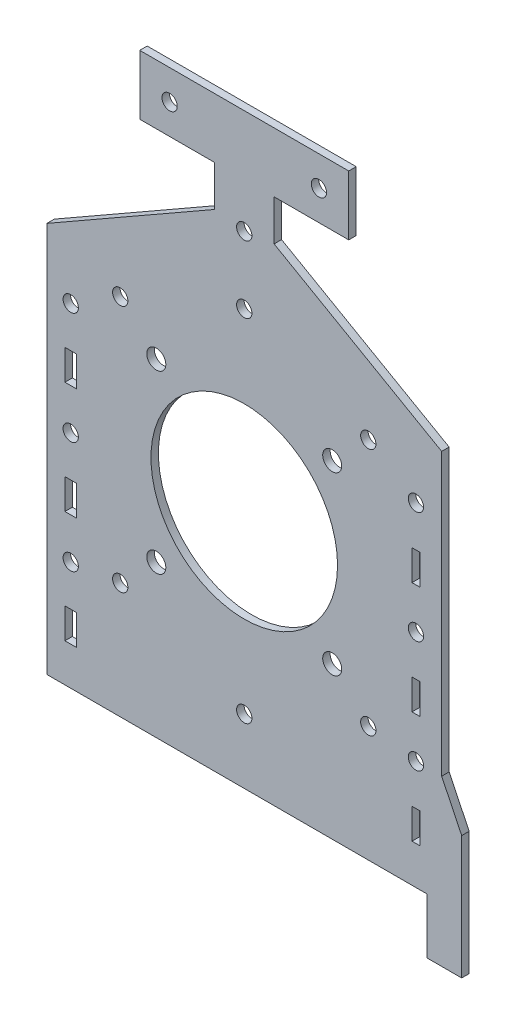
SolidWorks part; units mm, degrees
ref_plane "前视基准面" through (0, 0, 0) normal (0, 0, 1) x (1, 0, 0)
ref_plane "上视基准面" through (0, 0, 0) normal (0, 1, 0) x (1, 0, 0)
ref_plane "右视基准面" through (0, 0, 0) normal (1, 0, 0) x (0, 0, -1)
sketch "草图1" plane through (0, 0, 0) normal (0, 0, 1) x (1, 0, 0)
  line L0 (0, -36.5) -> (-46, -36.5) construction
  line L1 (52.9, 53.8832) -> (52.9, -21.5)
  line L29 (-52.9, 53.8832) -> (-52.9, -50.79)
  line L32 (0, 63.5) -> (0, -36.5) construction
  line L33 (-23.57, 37.07) -> (-23.57, -10.07) construction
  line L34 (23.57, 37.07) -> (23.57, -10.07) construction
  line L52 (-52.9, 53.8832) -> (52.9, 53.8832) construction
  line L60 (0, 78.5) -> (0, 84.5) construction
  line L61 (-28, 106.5) -> (28, 106.5)
  line L62 (28, 106.5) -> (28, 90.5)
  line L63 (28, 90.5) -> (8, 90.5)
  line L64 (8, 90.5) -> (8, 79.5697)
  line L65 (-28, 106.5) -> (-28, 90.5)
  line L66 (-28, 90.5) -> (-8, 90.5)
  line L67 (-8, 90.5) -> (-8, 79.5697)
  line L69 (48.9187, -50.79) -> (48.9187, -65.6422)
  line L70 (48.9187, -65.6422) -> (58.27, -65.6422)
  line L75 (58.27, -65.6422) -> (58.27, -32.5909)
  line L76 (-52.9, 53.8832) -> (-8, 79.5697)
  line L77 (8, 79.5697) -> (52.9, 53.8832)
  line L78 (46, 8.5) -> (43.95, 8.5) construction
  line L79 (47.05, 19.45) -> (44.95, 27.55) construction
  line L80 (47.05, 27.55) -> (44.95, 19.45) construction
  line L81 (46, -6.5) -> (44.95, -6.5) construction
  line L82 (47.05, -10.55) -> (44.95, -2.45) construction
  line L83 (47.05, -2.45) -> (44.95, -10.55) construction
  line L84 (47.05, -40.55) -> (44.95, -32.45) construction
  line L85 (47.05, -32.45) -> (44.95, -40.55) construction
  line L86 (46, -21.5) -> (43.95, -21.5) construction
  line L87 (47.05, 19.45) -> (44.95, 19.45)
  line L88 (47.05, 19.45) -> (47.05, 27.55)
  line L89 (47.05, 27.55) -> (44.95, 27.55)
  line L90 (44.95, 19.45) -> (44.95, 27.55)
  line L91 (47.05, -10.55) -> (44.95, -10.55)
  line L92 (47.05, -10.55) -> (47.05, -2.45)
  line L93 (47.05, -2.45) -> (44.95, -2.45)
  line L94 (44.95, -10.55) -> (44.95, -2.45)
  line L95 (44.95, -32.45) -> (44.95, -40.55)
  line L96 (47.05, -40.55) -> (44.95, -40.55)
  line L97 (47.05, -32.45) -> (47.05, -40.55)
  line L98 (47.05, -32.45) -> (44.95, -32.45)
  line L99 (58.27, -32.5909) -> (52.9, -21.5)
  line L101 (-44.95, 27.55) -> (-48.05, 27.55)
  line L122 (-52.9, -50.79) -> (-43.7092, -50.79)
  line L126 (-34.4034, -50.79) -> (48.9187, -50.79)
  line L131 (-43.7092, -50.79) -> (-34.4034, -50.79)
  line L139 (-44.95, 19.45) -> (-48.05, 19.45)
  line L140 (-44.95, 27.55) -> (-44.95, 19.45)
  line L141 (-48.05, 27.55) -> (-48.05, 19.45)
  line L142 (-44.95, -2.45) -> (-44.95, -10.55)
  line L143 (-44.95, -10.55) -> (-48.05, -10.55)
  line L144 (-44.95, -2.45) -> (-48.05, -2.45)
  line L145 (-48.05, -2.45) -> (-48.05, -10.55)
  line L146 (-44.95, -32.45) -> (-48.05, -32.45)
  line L147 (-44.95, -40.55) -> (-48.05, -40.55)
  line L148 (-44.95, -32.45) -> (-44.95, -40.55)
  line L149 (-48.05, -32.45) -> (-48.05, -40.55)
  circle A7 centre (-23.57, 37.07) radius 2.55
  circle A10 centre (-23.57, -10.07) radius 2.55
  circle A11 centre (23.57, -10.07) radius 2.55
  circle A12 centre (23.57, 37.07) radius 2.55
  circle A16 centre (0, 13.5) radius 25
  circle A17 centre (0, 13.5) radius 47 construction
  circle A18 centre (0, 60.5) radius 2.05
  circle A41 centre (33.234, 46.734) radius 2.05
  circle A43 centre (33.234, -19.734) radius 2.05
  circle A44 centre (0, -33.5) radius 2.05
  circle A45 centre (-33.234, -19.734) radius 2.05
  circle A47 centre (-33.234, 46.734) radius 2.05
  circle A48 centre (0, 78.5) radius 2.05
  circle A50 centre (-20, 98.5) radius 2.05
  circle A51 centre (20, 98.5) radius 2.05
  circle A52 centre (-47, 13.5) radius 2.05 construction
  circle A53 centre (47, 13.5) radius 2.05 construction
  circle A56 centre (46, 8.5) radius 2.05
  circle A57 centre (46, -21.5) radius 2.05
  circle A59 centre (46, 38.5) radius 2.05
  circle A63 centre (-46.5, -21.5) radius 2.05
  circle A64 centre (-46.5, 8.5) radius 2.05
  circle A65 centre (-46.5, 38.5) radius 2.05
  dimension "D3" = 5.1
  dimension "D6" = 23.57
  dimension "D10" = 65
  dimension "D16" = 4.1
  dimension "D27" = 50
  dimension "D4" = 46
  dimension "D5" = 8
  dimension "D7" = 47.14
  dimension "D12" = 50
  dimension "D17" = 20
  dimension "D18" = 20
  dimension "D19" = 20
  dimension "D20" = 20
  dimension "D21" = 8
  dimension "D22" = 8
  dimension "D23" = 8
  dimension "D24" = 8
  dimension "D25" = 8
  dimension "D26" = 8
extrude "凸台-拉伸1" add sketch "草图1" along normal blind 2
